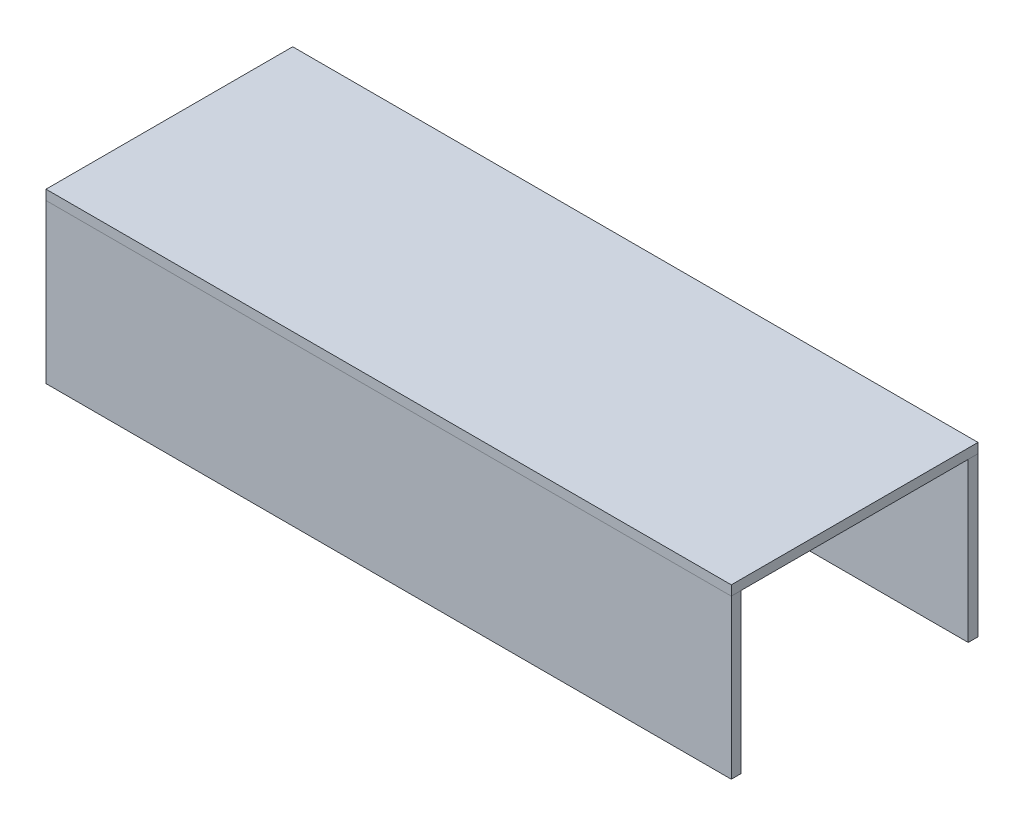
SolidWorks part; units mm, degrees
ref_plane "Front Plane" through (0, 0, 0) normal (0, 0, 1) x (1, 0, 0)
ref_plane "Top Plane" through (0, 0, 0) normal (0, 1, 0) x (1, 0, 0)
ref_plane "Right Plane" through (0, 0, 0) normal (1, 0, 0) x (0, 0, -1)
sketch "Sketch1" plane through (0, 0, 0) normal (0, 0, 1) x (1, 0, 0)
  line L1 (-58.1953, 35.4394) -> (17441.8047, 35.4394)
  line L2 (-58.1953, 35.4394) -> (-58.1953, -4264.5606)
  line L3 (-58.1953, -4264.5606) -> (17441.8047, -4264.5606)
  line L4 (17441.8047, 35.4394) -> (17441.8047, -4264.5606)
sketch "Sketch4" plane through (0, 0, 0) normal (1, 0, 0) x (0, 0, -1)
  line L1 (0, 0) -> (-6300, 0)
  line L2 (0, 0) -> (0, -250)
  line L3 (0, -250) -> (-6300, -250)
  line L4 (-6300, 0) -> (-6300, -250)
  dimension "D1" = 250
extrude "Boss-Extrude4" add sketch "Sketch4" along normal blind 17500
sketch "Sketch6" plane through (0, 0, 0) normal (1, 0, 0) x (0, 0, -1)
  line L1 (-6300, -250) -> (-6050, -250)
  line L2 (-6300, -250) -> (-6300, -4300)
  line L3 (-6300, -4300) -> (-6050, -4300)
  line L4 (-6050, -250) -> (-6050, -4300)
  dimension "D1" = 4050
  dimension "D2" = 250
extrude "Boss-Extrude5" add sketch "Sketch6" along normal blind 17500 separate body
sketch "Sketch7" plane through (0, 0, 0) normal (1, 0, 0) x (0, 0, -1)
  line L1 (0, -250) -> (-250, -250)
  line L2 (0, -250) -> (0, -4300)
  line L3 (0, -4300) -> (-250, -4300)
  line L4 (-250, -250) -> (-250, -4300)
  dimension "D1" = 250
extrude "Boss-Extrude6" add sketch "Sketch7" along normal blind 17500 separate body
